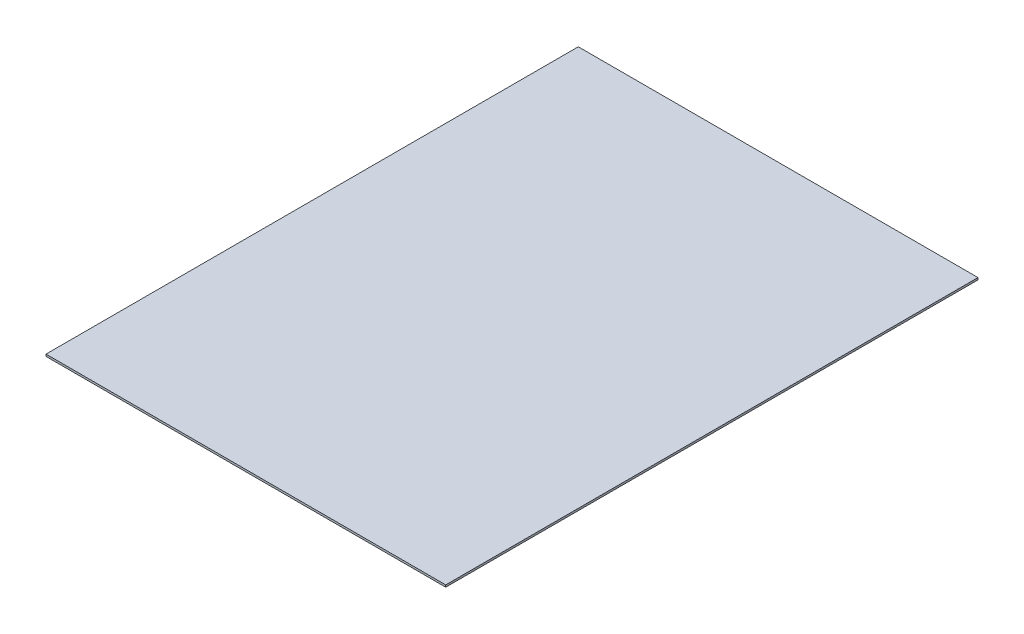
SolidWorks part; units mm, degrees
material "Pine"
ref_plane "Front Plane" through (0, 0, 0) normal (0, 0, 1) x (1, 0, 0)
ref_plane "Top Plane" through (0, 0, 0) normal (0, 1, 0) x (1, 0, 0)
ref_plane "Right Plane" through (0, 0, 0) normal (1, 0, 0) x (0, 0, -1)
sketch "Sketch1" plane through (0, 0, 0) normal (0, 1, 0) x (1, 0, 0)
  line L0 (0, 0) -> (622.3, 0)
  line L1 (0, 0) -> (0, 828.675)
  line L2 (622.3, 0) -> (622.3, 828.675)
  line L3 (0, 828.675) -> (622.3, 828.675)
  dimension "D1" = 828.675
  dimension "D2" = 622.3
extrude "Boss-Extrude1" add sketch "Sketch1" along normal blind 3.175
